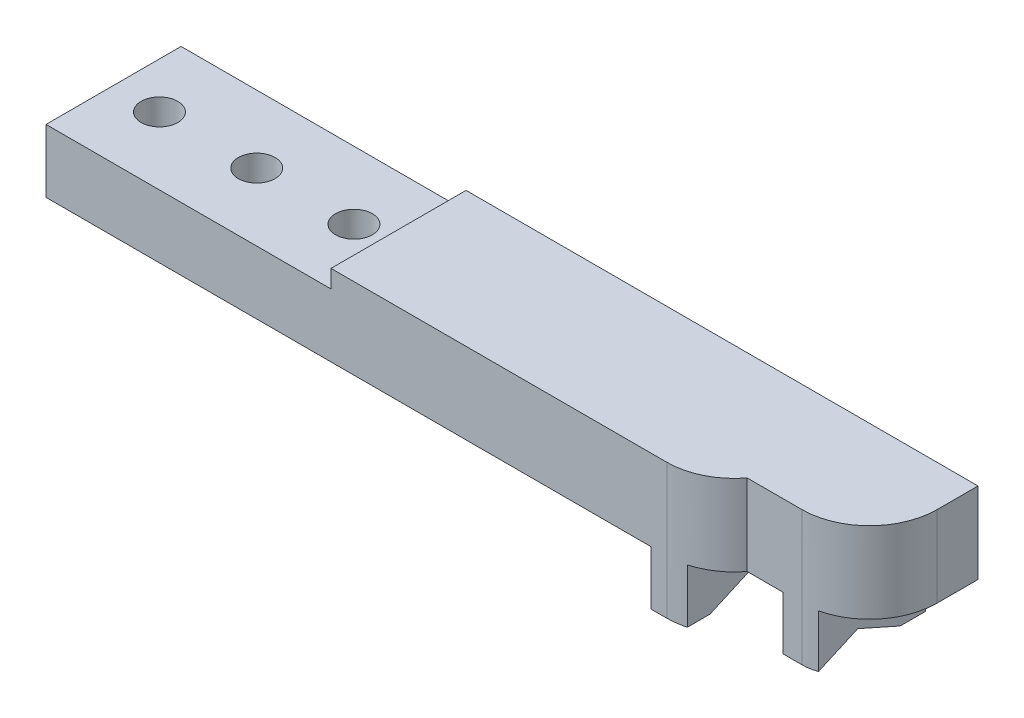
SolidWorks part; units mm, degrees
material "4140"
ref_plane "Alzado" through (0, 0, 0) normal (0, 0, 1) x (1, 0, 0)
ref_plane "Planta" through (0, 0, 0) normal (0, 1, 0) x (1, 0, 0)
ref_plane "Vista lateral" through (0, 0, 0) normal (1, 0, 0) x (0, 0, -1)
sketch "Croquis1" plane through (0, 0, 0) normal (0, 1, 0) x (1, 0, 0)
  line L1 (0, -12.7) -> (74.93, -12.7)
  line L2 (0, -12.7) -> (0, 0)
  line L3 (0, 0) -> (74.93, 0)
  line L4 (74.93, -12.7) -> (74.93, 0)
  line L5 (37.465, 0) -> (37.465, -12.7) construction
  line L6 (0, -6.35) -> (74.93, -6.35) construction
  point P264 (37.465, -6.35)
  dimension "D1" = 74.93
  dimension "D2" = 12.7
extrude "Saliente-Extruir1" add sketch "Croquis1" along normal blind 12.7
sketch "Croquis2" plane through (0, 0, 12.7) normal (0, 0, 1) x (1, 0, 0)
  line L0 (0, 0) -> (74.93, 0) construction
  line L1 (0, 12.7) -> (26.797, 12.7)
  line L2 (0, 12.7) -> (0, 11.0236)
  line L3 (0, 11.0236) -> (26.797, 11.0236)
  line L4 (26.797, 12.7) -> (26.797, 11.0236)
  line L5 (13.3985, 11.0236) -> (13.3985, 12.7) construction
  line L6 (0, 11.8618) -> (26.797, 11.8618) construction
  line L7 (60.071, 0) -> (66.802, 0)
  line L8 (60.071, 0) -> (60.071, 5.08)
  line L9 (60.071, 5.08) -> (66.802, 5.08)
  line L10 (66.802, 0) -> (66.802, 5.08)
  line L11 (63.4365, 5.08) -> (63.4365, 0) construction
  line L12 (60.071, 2.54) -> (66.802, 2.54) construction
  line L13 (0, 12.7) -> (74.93, 12.7) construction
  line L14 (0, 0) -> (56.896, 0)
  line L15 (0, 0) -> (0, 5.08)
  line L16 (0, 5.08) -> (56.896, 5.08)
  line L17 (56.896, 0) -> (56.896, 5.08)
  line L18 (28.448, 5.08) -> (28.448, 0) construction
  line L19 (0, 2.54) -> (56.896, 2.54) construction
  line L20 (74.93, 0) -> (69.977, 0)
  line L21 (74.93, 0) -> (74.93, 5.08)
  line L22 (74.93, 5.08) -> (69.977, 5.08)
  line L23 (69.977, 0) -> (69.977, 5.08)
  line L24 (72.4535, 5.08) -> (72.4535, 0) construction
  line L25 (74.93, 2.54) -> (69.977, 2.54) construction
  line L26 (74.93, 12.7) -> (74.93, 0) construction
  point P26 (28.448, 2.54)
  point P132 (63.4365, 2.54)
  point P188 (13.3985, 11.8618)
  point P212 (72.4535, 2.54)
  dimension "D1" = 7.62
  dimension "D2" = 48.133
  dimension "D3" = 1.6764
  dimension "D4" = 4.953
  dimension "D5" = 8.128
  dimension "D6" = 14.859
  dimension "D7" = 18.034
extrude "Cortar-Extruir1" cut sketch "Croquis2" against normal through all
hole_wizard "Taladro roscado #8-321" positions "Croquis3" profile "Croquis5" tap size "#8-32" standard "Ansi Inch" end condition through all
sketch "Croquis3" plane through (0, 5.08, 0) normal (0, -1, 0) x (-1, 0, 0)
  line L0 (-22.606, -6.35) -> (-4.318, -6.35) construction
  line L2 (-56.896, -12.7) -> (0, -12.7) construction
  line L3 (-74.93, 0) -> (-74.93, -12.7) construction
  point P0 (-4.318, -6.35)
  point P2 (-13.462, -6.35)
  point P4 (-22.606, -6.35)
  dimension "D1" = 6.35
  dimension "D2" = 52.324
  dimension "D3" = 70.612
sketch "Croquis5" plane through (4.318, 5.08, 6.35) normal (1, 0, 0) x (0, 0, -1)
  line L0 (0, 0) -> (0, 7.62)
  line L1 (0, 7.62) -> (1.7272, 7.62)
  line L2 (1.7272, 7.62) -> (1.7272, 0)
  line L5 (1.7272, 0) -> (0, 0)
  line L11 (0, -6.35) -> (0, 107.95) construction
  dimension "Diámetro de perforador para roscar hasta el siguiente" = 3.4544
  dimension "Profundidad de perforador para roscar hasta el siguiente" = 7.62
cosmetic thread "Rosca de taladro1" parameters "D2"=4.1656
cosmetic thread "Rosca de taladro2" parameters "D2"=4.1656
cosmetic thread "Rosca de taladro3" parameters "D2"=4.1656
sketch "Croquis6" plane through (0, 0, 0) normal (0, -1, 0) x (1, 0, 0)
  line L0 (74.93, 0) -> (74.93, 12.7) construction
  line L2 (68.58, 10.2) -> (63.4238, 10.2)
  line L3 (66.802, 12.7) -> (60.071, 12.7) construction
  line L4 (66.802, 12.7) -> (69.977, 12.7) construction
  line L5 (58.374, 12.7) -> (74.93, 12.7)
  line L6 (74.93, 12.7) -> (74.93, 3.85)
  arc A0 (74.93, 3.85) -> (68.58, 10.2) centre (68.58, 3.85) ccw
  arc A1 (63.4238, 10.2) -> (58.374, 12.7) centre (58.374, 6.35) ccw
  dimension "D1" = 6.35
  dimension "D2" = 11.5062
  dimension "D3" = 2.5
extrude "Cortar-Extruir2" cut sketch "Croquis6" against normal through all
sketch "Croquis7" plane through (74.93, 0, 0) normal (1, 0, 0) x (0, 0, -1)
  line L0 (-2.3622, 0) -> (-6.35, 1.778)
  line L1 (0, 0) -> (-10.0444, 0) construction
  line L2 (-6.35, 1.778) -> (-10.3378, 0)
  line L3 (0, 0) -> (-12.4691, 0) construction
  line L4 (-10.3378, 0) -> (-2.3622, 0)
  line L5 (0, 8.89) -> (-12.7, 8.89) construction
  line L6 (0, 12.7) -> (0, 5.08) construction
  line L7 (-12.7, 12.7) -> (-12.7, 0) construction
  line L8 (-6.35, 8.89) -> (-6.35, 1.778) construction
  line L9 (-6.35, 1.778) -> (-6.35, 0) construction
  dimension "D1" = 3.9878
  dimension "D2" = 1.778
extrude "Cortar-Extruir3" cut sketch "Croquis7" against normal through all
